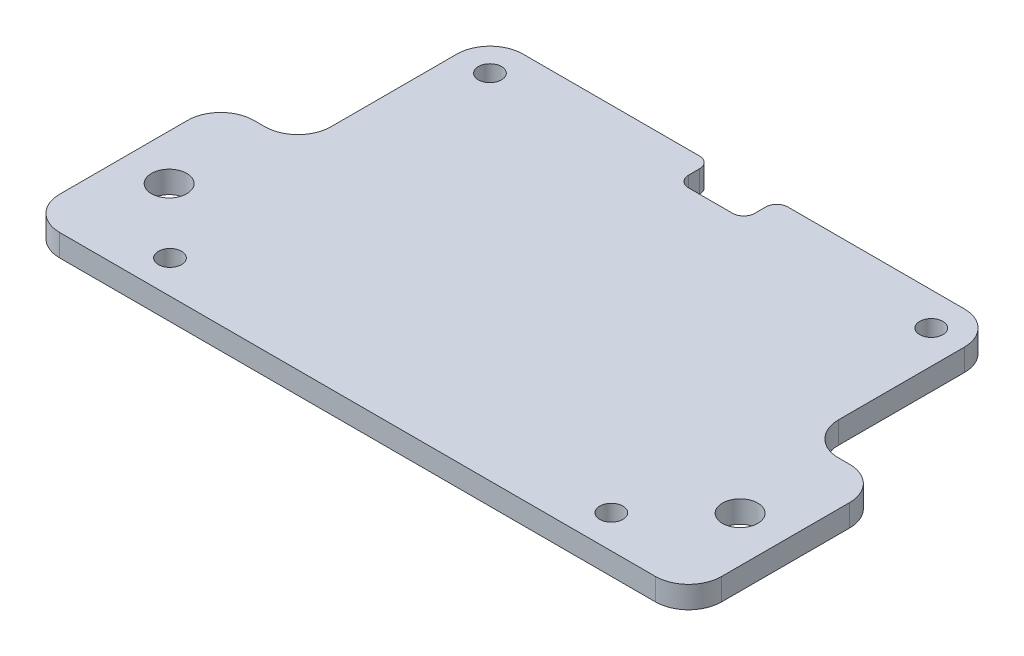
SolidWorks part; units mm, degrees
ref_plane "Front Plane" through (0, 0, 0) normal (0, 0, 1) x (1, 0, 0)
ref_plane "Top Plane" through (0, 0, 0) normal (0, 1, 0) x (1, 0, 0)
ref_plane "Right Plane" through (0, 0, 0) normal (1, 0, 0) x (0, 0, -1)
sketch "Sketch1" plane through (0, 0, 0) normal (0, 1, 0) x (1, 0, 0)
  line L0 (-27.0606, 17.5) -> (-27.0606, 14.5)
  line L1 (-0.0606, -17.5) -> (-30.0606, -17.5)
  line L2 (-53.0606, 0.1) -> (-53.0606, 17.5)
  line L3 (-53.0606, 17.5) -> (-33.0606, 17.5)
  line L4 (-7.0606, 0.1) -> (-7.0606, 17.5)
  line L5 (-27.0606, 17.5) -> (-7.0606, 17.5)
  line L6 (-53.0606, 17.5) -> (-33.0606, 17.5) construction
  line L7 (-30.0606, -17.5) -> (-60.0606, -17.5)
  line L8 (-10.0606, -17.5) -> (-50.0606, -17.5) construction
  line L9 (-27.0606, 14.5) -> (-33.0606, 14.5)
  line L10 (-7.0606, 0.1) -> (-0.0606, 0.1)
  line L11 (-0.0606, -17.5) -> (-0.0606, 0.1)
  line L12 (-33.0606, 14.5) -> (-33.0606, 17.5)
  line L13 (-27.0606, 17.5) -> (-7.3106, 17.5) construction
  line L14 (-53.0606, 0.1) -> (-60.0606, 0.1)
  line L15 (-60.0606, -17.5) -> (-60.0606, 0.1)
  circle A0 centre (-4.1856, -8.7) radius 1.6
  circle A1 centre (-55.9356, -8.7) radius 1.6
  circle A2 centre (-10.0606, -14.5) radius 1.05
  circle A3 centre (-50.0606, -14.5) radius 1.05
  circle A4 centre (-50.0606, 14.5) radius 1.05
  circle A5 centre (-10.0606, 14.5) radius 1.05
  dimension "D6" = 3.2
  dimension "D7" = 8.8
  dimension "D13" = 3
  dimension "D15" = 2.1
  dimension "D1" = 7
  dimension "D2" = 30
  dimension "D3" = 7
  dimension "D4" = 17.6
  dimension "D5" = 30
  dimension "D8" = 4.125
  dimension "D9" = 4.125
  dimension "D10" = 8.8
  dimension "D11" = 35
  dimension "D12" = 60
  dimension "D14" = 6
  dimension "D16" = 3
  dimension "D17" = 10
  dimension "D18" = 3
  dimension "D19" = 10
  dimension "D20" = 3
  dimension "D21" = 32
  dimension "D22" = 32
  dimension "D23" = 3
extrude "Boss-Extrude1" add sketch "Sketch1" along normal blind 2
fillet "Fillet1" radius 3 8 edges at (-0.0606, 1, 17.5) (-0.0606, 1, -0.1) (-53.0606, 1, -0.1) (-7.0606, 1, -0.1) (-7.0606, 1, -17.5) (-53.0606, 1, -17.5) (-60.0606, 1, -0.1) (-60.0606, 1, 17.5)
fillet "Fillet2" radius 1 4 edges at (-33.0606, 1, -17.5) (-33.0606, 1, -14.5) (-27.0606, 1, -14.5) (-27.0606, 1, -17.5)
